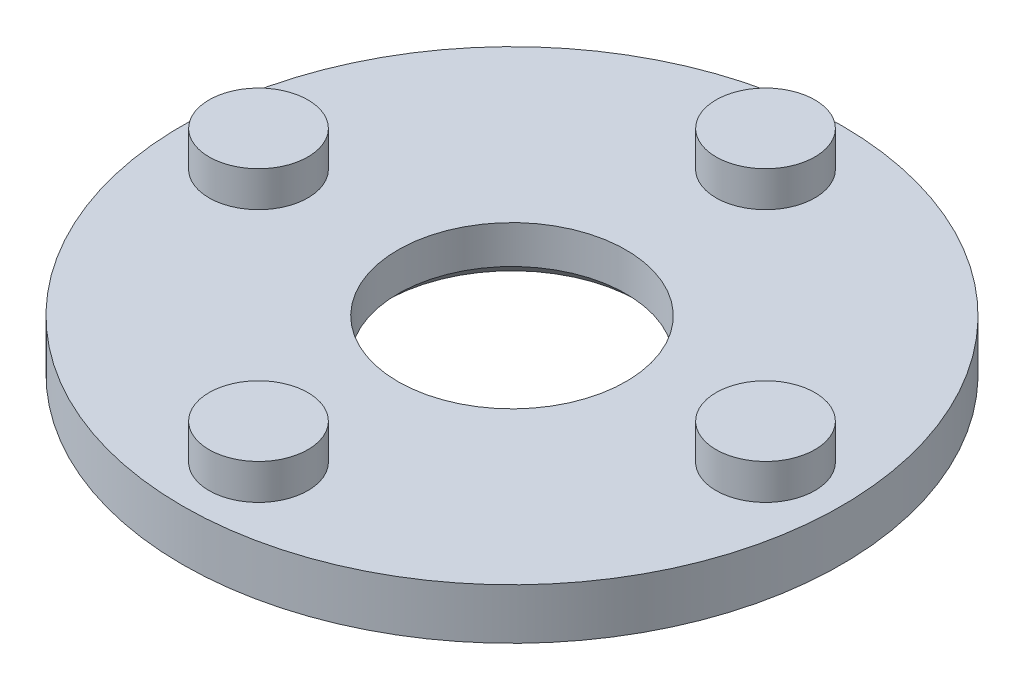
SolidWorks part; units mm, degrees
ref_plane "Front Plane" through (0, 0, 0) normal (0, 0, 1) x (1, 0, 0)
ref_plane "Top Plane" through (0, 0, 0) normal (0, 1, 0) x (1, 0, 0)
ref_plane "Right Plane" through (0, 0, 0) normal (1, 0, 0) x (0, 0, -1)
sketch "Sketch1" plane through (0, 0, 0) normal (0, 1, 0) x (1, 0, 0)
  circle A0 centre (0, 0) radius 13
  dimension "D1" = 26
extrude "Boss-Extrude1" add sketch "Sketch1" along normal blind 2
sketch "Sketch2" plane through (0, 2, 0) normal (0, 1, 0) x (1, 0, 0)
  circle A0 centre (0, 0) radius 4.5
  dimension "D1" = 9
extrude "Cut-Extrude1" cut sketch "Sketch2" against normal through all
sketch "Sketch3" plane through (0, 2, 0) normal (0, 1, 0) x (1, 0, 0)
  circle A0 centre (0, 0) radius 10 construction
  circle A1 centre (0, 10) radius 1.95
  circle A2 centre (10, 0) radius 1.95
  circle A3 centre (-10, 0) radius 1.95
  circle A4 centre (0, -10) radius 1.95
  dimension "D1" = 20
  dimension "D2" = 3.9
extrude "Boss-Extrude2" add sketch "Sketch3" along normal blind 1.4
chamfer "Chamfer1" distance 0.5 angle 45 1 edges at (0, 0, 4.5)
